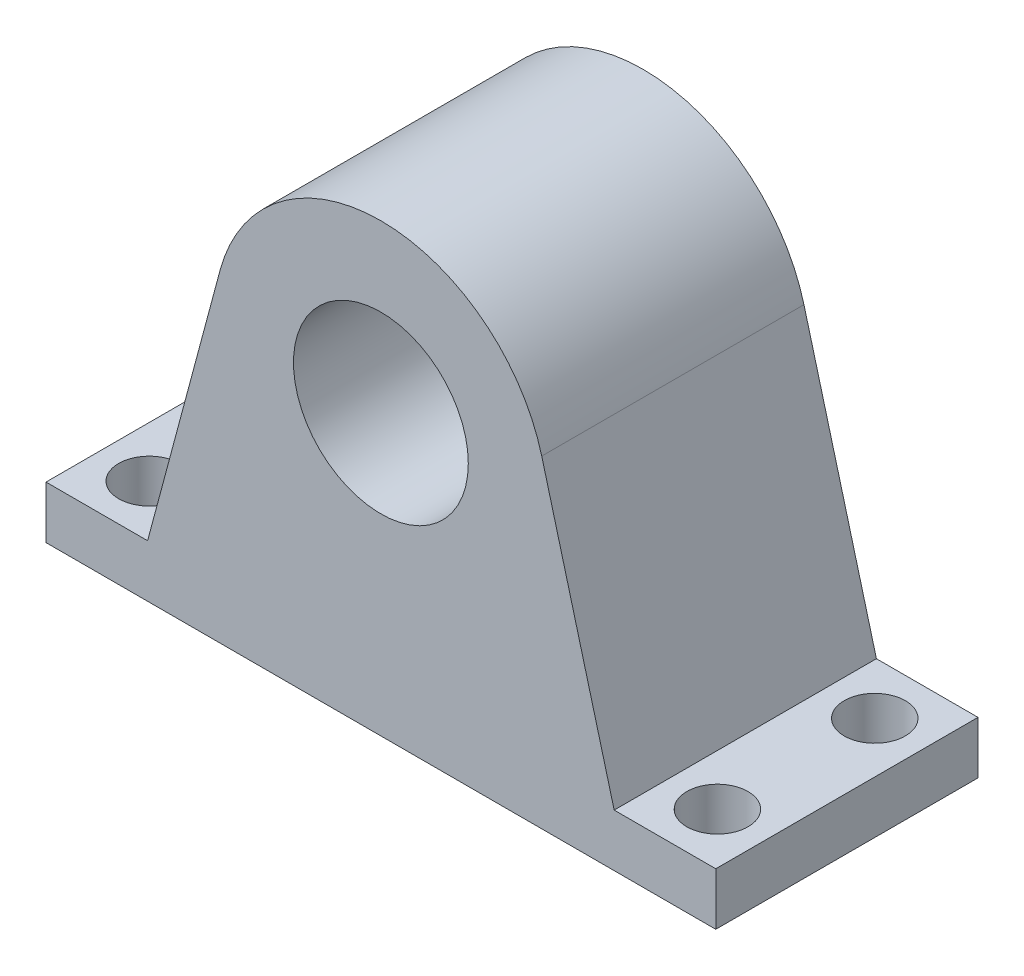
SolidWorks part; units mm, degrees
ref_plane "Front Plane" through (0, 0, 0) normal (0, 0, 1) x (1, 0, 0)
ref_plane "Top Plane" through (0, 0, 0) normal (0, 1, 0) x (1, 0, 0)
ref_plane "Right Plane" through (0, 0, 0) normal (1, 0, 0) x (0, 0, -1)
sketch "Sketch1" plane through (0, 0, 0) normal (0, 0, 1) x (1, 0, 0)
  line L0 (0, 0) -> (-38.3113, 0)
  line L3 (0, 0) -> (0, 32) construction
  line L5 (0, 0) -> (38.3113, 0)
  line L12 (-26.6887, 6) -> (-18.4009, 36.9305)
  line L13 (18.4009, 36.9305) -> (26.6887, 6)
  line L15 (-26.6887, 6) -> (-38.3113, 6)
  line L16 (-38.3113, 6) -> (-38.3113, 0)
  line L17 (26.6887, 6) -> (38.3113, 6)
  line L18 (38.3113, 6) -> (38.3113, 0)
  arc A0 (18.4009, 36.9305) -> (-18.4009, 36.9305) centre (0, 32) ccw
  circle A2 centre (0, 32) radius 32 construction
  point P1 (32.5, 6)
  point P11 (-32.5, 6)
  dimension "D1" = 38.1
  dimension "D5" = 32
  dimension "D2" = 6
  dimension "D3" = 105
  dimension "D4" = 65
extrude "Boss-Extrude1" add sketch "Sketch1" along normal blind 30 contours A0 L12 L15 L16 L0 L5 L18 L17 L13
hole_wizard "Ø20.0mm Dowel Hole1" positions "3DSketch1" profile "Sketch3" hole size "Ø20.0" standard "ANSI Metric"
sketch3d "3DSketch1"
  line L0 (0, 32, 30) -> (0, 32, 0) construction
  point P0 (0, 32, 30)
sketch "Sketch3" plane through (0, 32, 30) normal (1, 0, 0) x (0, -1, 0)
  line L0 (0, 0) -> (0, 80.0877)
  line L1 (0, 80.0877) -> (10, 74.0791)
  line L2 (10, 74.0791) -> (10, 0)
  line L5 (10, 0) -> (0, 0)
  line L10 (0, 80.0877) -> (-10, 74.0791) construction
  line L11 (0, -6.35) -> (0, 107.95) construction
  dimension "Hole Dia." = 20
  dimension "Hole Depth" = 74.0791
  dimension "Drill Angle" = 118
sketch "Sketch4" plane through (0, 6, 0) normal (0, 1, 0) x (1, 0, 0)
  line L0 (-32.5, -6) -> (-32.5, -24) construction
  line L1 (-26.6887, 0) -> (-38.3113, 0) construction
  line L2 (-26.6887, 0) -> (-38.3113, 0) construction
  line L3 (-38.3113, -30) -> (-38.3113, 0) construction
  line L4 (-38.3113, -30) -> (-38.3113, 0) construction
  line L5 (-38.3113, -15) -> (-32.5, -15) construction
  point P0 (-32.5, -6)
  point P1 (-32.5, -24)
  dimension "D1" = 18
hole_wizard "M8x1.0 Tapped Hole1" positions "3DSketch2" profile "Sketch6" tap size "M8x1.0" standard "ANSI Metric"
sketch3d "3DSketch2"
  point P0 (-32.5, 6, 6)
  point P3 (-32.5, 6, 24)
sketch "Sketch6" plane through (-32.5, 6, 6) normal (1, 0, 0) x (0, 0, 1)
  line L0 (0, 0) -> (0, 21.103)
  line L1 (0, 21.103) -> (3.5, 19)
  line L2 (3.5, 19) -> (3.5, 0)
  line L5 (3.5, 0) -> (0, 0)
  line L10 (0, 21.103) -> (-3.5, 19) construction
  line L11 (0, -6.35) -> (0, 107.95) construction
  dimension "Tap Drill Dia." = 7
  dimension "Tap Drill Depth" = 19
  dimension "Drill Angle" = 118
cosmetic thread "Hole Thread1" parameters "D1"=16, "D2"=8
cosmetic thread "Hole Thread2" parameters "D1"=16, "D2"=8
mirror "Mirror1" about plane through (0, 0, 0) normal (1, 0, 0) of "M8x1.0 Tapped Hole1"
cosmetic thread "Hole Thread3" parameters "D1"=16, "D2"=8
cosmetic thread "Hole Thread4" parameters "D1"=16, "D2"=8
